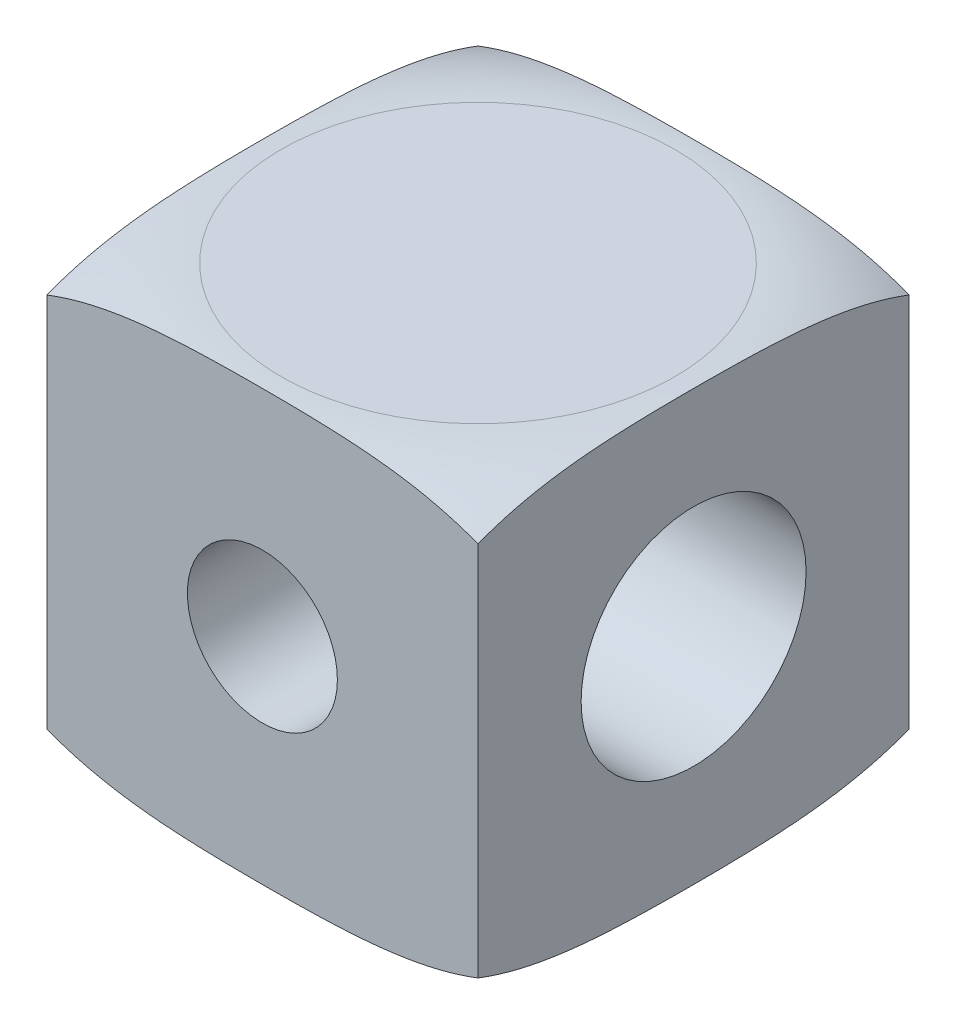
SolidWorks part; units mm, degrees
material "Plain Carbon Steel"
ref_plane "Front Plane" through (0, 0, 0) normal (0, 0, 1) x (1, 0, 0)
ref_plane "Top Plane" through (0, 0, 0) normal (0, 1, 0) x (1, 0, 0)
ref_plane "Right Plane" through (0, 0, 0) normal (1, 0, 0) x (0, 0, -1)
sketch "Sketch1" plane through (0, 0, 0) normal (0, 1, 0) x (1, 0, 0)
  line L1 (-2.875, -2.875) -> (2.875, -2.875)
  line L2 (-2.875, -2.875) -> (-2.875, 2.875)
  line L3 (-2.875, 2.875) -> (2.875, 2.875)
  line L4 (2.875, -2.875) -> (2.875, 2.875)
  line L5 (-2.875, -2.875) -> (2.875, 2.875) construction
  line L6 (-2.875, 2.875) -> (2.875, -2.875) construction
  point P0 (0, 0)
  dimension "D1" = 5.75
  dimension "D2" = 5.75
extrude "Boss-Extrude1" add sketch "Sketch1" along normal mid plane 5.75
sketch "Sketch2" plane through (0, 0, 2.875) normal (0, 0, 1) x (1, 0, 0)
  circle A0 centre (0, 0) radius 1
  dimension "D1" = 2
extrude "Cut-Extrude1" cut sketch "Sketch2" against normal up to next
sketch "Sketch3" plane through (-2.875, 0, 0) normal (-1, 0, 0) x (0, 0, 1)
  circle A0 centre (0, 0) radius 1.5
  dimension "D1" = 3
extrude "Cut-Extrude2" cut sketch "Sketch3" against normal through all
sketch "Sketch4" plane through (0, 0, 0) normal (0, 0, 1) x (1, 0, 0)
  line L0 (2.625, 2.875) -> (5.625, 2.875)
  line L1 (-2.875, 2.875) -> (2.875, 2.875) construction
  line L2 (5.625, 2.875) -> (5.625, -0.125)
  line L3 (2.875, 2.875) -> (2.875, -2.875) construction
  line L4 (0, 0) -> (0, 50000) construction
  arc A0 (2.625, 2.875) -> (5.625, -0.125) centre (2.625, -0.125) cw
  dimension "D1" = 0.25
  dimension "D2" = 3
  dimension "D3" = 3
revolve "Cut-Revolve1" cut sketch "Sketch4" angle 360 about L4
mirror "Mirror1" about plane through (0, 0, 0) normal (0, 1, 0) of "Cut-Revolve1"
